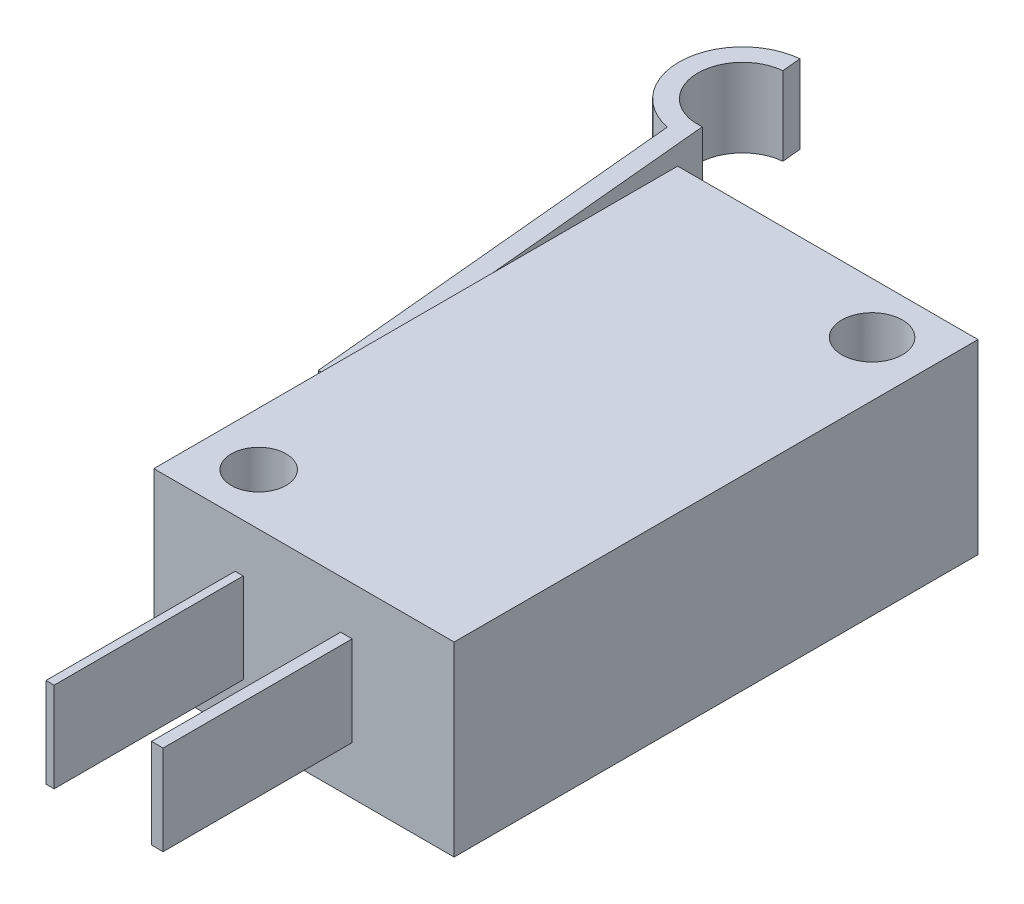
SolidWorks part; units mm, degrees
ref_plane "Front Plane" through (0, 0, 0) normal (0, 0, 1) x (1, 0, 0)
ref_plane "Top Plane" through (0, 0, 0) normal (0, 1, 0) x (1, 0, 0)
ref_plane "Right Plane" through (0, 0, 0) normal (1, 0, 0) x (0, 0, -1)
sketch "Sketch1" plane through (0, 0, 0) normal (0, 1, 0) x (1, 0, 0)
  line L1 (0, 0) -> (15.88, 0)
  line L2 (0, 0) -> (0, 27.7)
  line L3 (0, 27.7) -> (15.88, 27.7)
  line L4 (15.88, 0) -> (15.88, 27.7)
  dimension "D1" = 27.7
  dimension "D2" = 15.88
extrude "Boss-Extrude1" add sketch "Sketch1" along normal blind 9.85
sketch "Sketch2" plane through (0, 0, 0) normal (0, 0, 1) x (1, 0, 0)
  line L1 (9.88, 7.3) -> (10.49, 7.3)
  line L2 (9.88, 7.3) -> (9.88, 2.55)
  line L3 (9.88, 2.55) -> (10.49, 2.55)
  line L4 (10.49, 7.3) -> (10.49, 2.55)
  line L6 (8.3675, 9.85) -> (8.3675, 0) construction
  line L7 (4.73, 7.3) -> (4.3, 7.3)
  line L8 (4.73, 7.3) -> (4.73, 2.55)
  line L9 (4.73, 2.55) -> (4.3, 2.55)
  line L10 (4.3, 7.3) -> (4.3, 2.55)
  line L11 (0, 9.85) -> (0, 0) construction
  line L12 (15.88, 9.85) -> (15.88, 0) construction
  line L13 (0, 9.85) -> (15.88, 9.85) construction
  line L14 (0, 0) -> (15.88, 0) construction
  line L15 (4.73, 4.925) -> (8.3675, 4.925) construction
  line L16 (8.3675, 4.925) -> (9.88, 4.925) construction
  dimension "D1" = 5.39
  dimension "D2" = 4.3
  dimension "D3" = 5.15
  dimension "D4" = 4.75
  dimension "D5" = 4.75
extrude "Boss-Extrude2" add sketch "Sketch2" along normal blind 10
sketch "Sketch4" plane through (0, 9.85, 0) normal (0, 1, 0) x (1, 0, 0)
  line L0 (0, 0) -> (15.88, 0) construction
  line L1 (0, 27.7) -> (0, 0) construction
  line L2 (15.88, 27.7) -> (0, 27.7) construction
  line L3 (15.88, 0) -> (15.88, 27.7) construction
  circle A0 centre (2.82, 2.725) radius 1.45
  circle A1 centre (12.98, 25) radius 1.6
  dimension "D1" = 2.9
  dimension "D2" = 2.725
  dimension "D4" = 3.2
  dimension "D3" = 2.82
  dimension "D5" = 2.7
  dimension "D6" = 2.9
extrude "Cut-Extrude1" cut sketch "Sketch4" against normal blind 10
sketch "Sketch5" plane through (0, 0, 0) normal (-1, 0, 0) x (0, 0, 1)
  line L0 (-11.7, 0) -> (-11.7, 9.85) construction
  line L1 (-11.7, 2.85) -> (-12.7, 2.85)
  line L2 (-11.7, 2.85) -> (-11.7, 7)
  line L3 (-11.7, 7) -> (-12.7, 7)
  line L4 (-12.7, 2.85) -> (-12.7, 7)
  line L5 (-27.7, 0) -> (0, 0) construction
  line L7 (-27.7, 9.85) -> (-27.7, 0) construction
  line L8 (-27.7, 9.85) -> (0, 9.85) construction
  point P12 (-11.7, 4.925)
  point P13 (-11.7, 4.925)
  dimension "D1" = 4.15
  dimension "D3" = 1
  dimension "D4" = 15
extrude "Boss-Extrude3" add sketch "Sketch5" along normal blind 3
sketch "Sketch7" plane through (0, 7, 0) normal (0, 1, 0) x (1, 0, 0)
  line L0 (-3, 11.7) -> (-5, 33)
  line L1 (-5, 33) -> (-4, 33)
  line L3 (-3, 11.7) -> (0, 11.7) construction
  line L4 (-2, 11.7) -> (-3, 11.7)
  line L5 (0, 27.7) -> (0, 0) construction
  line L6 (-4, 33) -> (-2, 11.7)
  line L7 (-4, 33) -> (-4.4417, 37.7044) construction
  line L8 (-4.4417, 37.7044) -> (-4.5352, 38.7)
  line L9 (-4, 33) -> (-3.9065, 32.0044)
  line L10 (-4, 33) -> (-5, 33)
  line L11 (-5, 33) -> (-4.9119, 32.0614)
  line L12 (-3, 12.7) -> (0, 12.7) construction
  line L13 (15.88, 27.7) -> (0, 27.7) construction
  circle A0 centre (-4.2209, 35.3522) radius 2.3625
  circle A1 centre (-4.2209, 35.3522) radius 3.3625
  dimension "D5" = 11
  dimension "D6" = 1
  dimension "D1" = 1
  dimension "D2" = 20.3
  dimension "D3" = 5
  dimension "D4" = 1
extrude "Boss-Extrude5" add sketch "Sketch7" against normal blind 4.15 contours L0 L1 L6 L4 | A1 | A0
sketch "Sketch8" plane through (0, 2.85, 0) normal (0, -1, 0) x (-1, 0, 0)
  line L0 (3.9065, 32.0044) -> (2.0939, 12.7) construction
  line L1 (3.9065, 32.0044) -> (-0.8969, 32.4554)
  line L2 (3.9065, 32.0044) -> (4.5352, 38.7)
  line L3 (4.5352, 38.7) -> (-0.2682, 39.151)
  line L4 (-0.8969, 32.4554) -> (-0.2682, 39.151)
  arc A0 (4.9119, 32.0614) -> (3.9065, 32.0044) centre (4.2209, 35.3522) ccw construction
  dimension "D1" = 4.8034
extrude "Cut-Extrude2" cut sketch "Sketch8" against normal through all
sketch "Sketch6" plane through (0, 0, -12.7) normal (0, 0, -1) x (-1, 0, 0)
  line L0 (2.0939, 7) -> (0, 7) construction
  line L1 (5, 2.85) -> (2, 2.85)
  line L2 (5, 2.85) -> (5, 7)
  line L3 (5, 7) -> (2, 7)
  line L4 (2, 2.85) -> (2, 7)
  line L5 (2.0939, 2.85) -> (0, 2.85) construction
  dimension "D1" = 3
